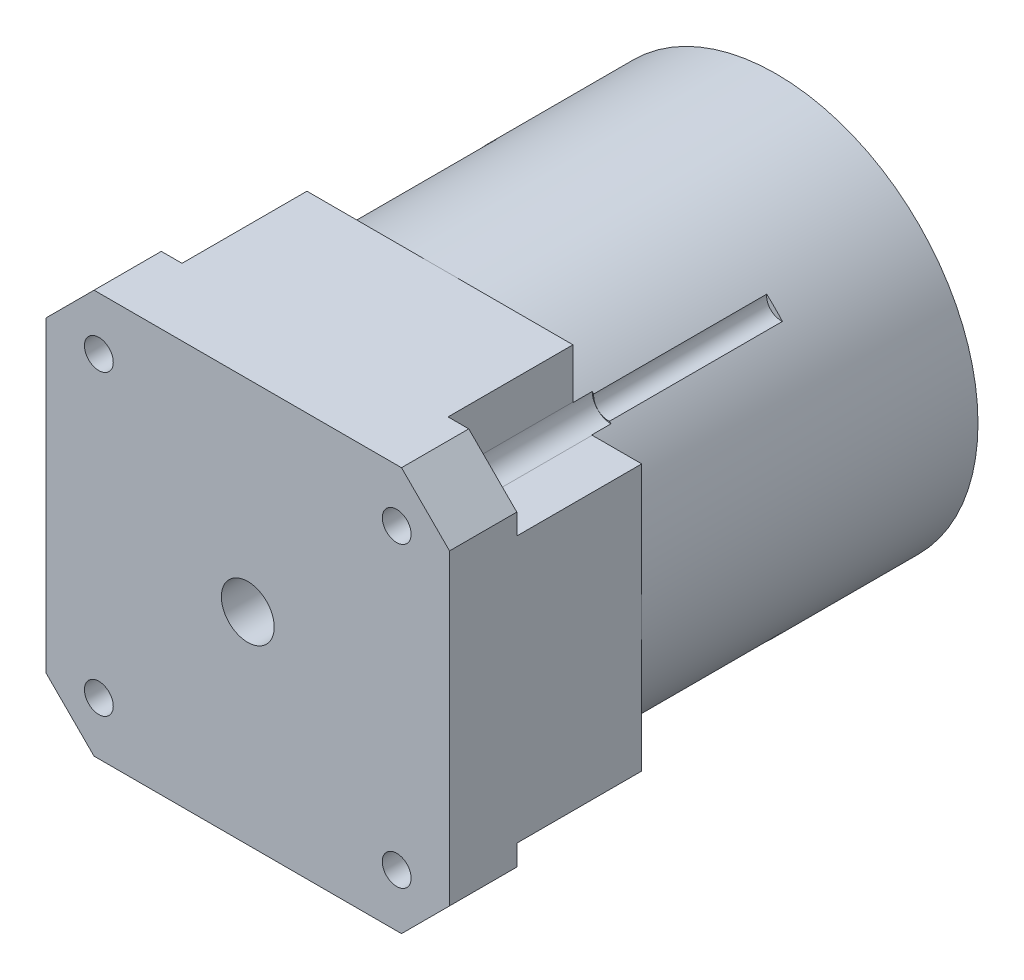
SolidWorks part; units mm, degrees
ref_plane "Front Plane" through (0, 0, 0) normal (0, 0, 1) x (1, 0, 0)
ref_plane "Top Plane" through (0, 0, 0) normal (0, 1, 0) x (1, 0, 0)
ref_plane "Right Plane" through (0, 0, 0) normal (1, 0, 0) x (0, 0, -1)
sketch "Sketch2" plane through (0, 0, 0) normal (0, 0, 1) x (1, 0, 0)
  circle A0 centre (0, 0) radius 21
  dimension "D1" = 42
extrude "Boss-Extrude1" add sketch "Sketch2" along normal blind 35
sketch "Sketch3" plane through (0, 0, 35) normal (0, 0, 1) x (1, 0, 0)
  line L1 (-21, -21) -> (21, -21)
  line L2 (-21, -21) -> (-21, 21)
  line L3 (-21, 21) -> (21, 21)
  line L4 (21, -21) -> (21, 21)
  line L5 (-21, -21) -> (21, 21) construction
  line L6 (-21, 21) -> (21, -21) construction
  point P0 (0, 0)
extrude "Boss-Extrude2" add sketch "Sketch3" along normal blind 20
chamfer "Chamfer1" distance 5 angle 45 4 edges at (-21, -21, 45) (21, -21, 45) (21, 21, 45) (-21, 21, 45)
sketch "Sketch4" plane through (0, 0, 35) normal (0, 0, -1) x (-1, 0, 0)
  line L0 (-14.9549, 0) -> (14.9549, 0) construction
  line L1 (0, 0) -> (0, 15.4444) construction
  circle A0 centre (15.5, 15.5) radius 1.5
  circle A1 centre (-15.5, 15.5) radius 1.5
  circle A2 centre (15.5, -15.5) radius 1.5
  circle A3 centre (-15.5, -15.5) radius 1.5
  point P6 (0, 0)
  dimension "D1" = 3
  dimension "D2" = 15.5
  dimension "D3" = 15.5
extrude "Cut-Extrude1" cut sketch "Sketch4" against normal through all and the other way blind 20
sketch "Sketch5" plane through (0, 0, 35) normal (0, 0, -1) x (-1, 0, 0)
  line L0 (21, 16) -> (16, 21) construction
  line L1 (15.8436, 13.8436) -> (23.1564, 13.8436)
  line L2 (13.8436, 15.8436) -> (13.8436, 23.1564)
  line L3 (13.8436, 23.1564) -> (23.1564, 23.1564)
  line L4 (23.1564, 13.8436) -> (23.1564, 23.1564)
  line L5 (13.8436, 13.8436) -> (23.1564, 23.1564) construction
  line L6 (13.8436, 23.1564) -> (23.1564, 13.8436) construction
  line L7 (0, 0) -> (0, 36.9408) construction
  line L8 (0, 0) -> (35.9646, 0) construction
  line L9 (13.8436, -23.1564) -> (23.1564, -13.8436) construction
  line L10 (13.8436, -13.8436) -> (23.1564, -23.1564) construction
  line L11 (23.1564, -13.8436) -> (23.1564, -23.1564)
  line L12 (13.8436, -23.1564) -> (23.1564, -23.1564)
  line L13 (13.8436, -15.8436) -> (13.8436, -23.1564)
  line L14 (15.8436, -13.8436) -> (23.1564, -13.8436)
  line L15 (-13.8436, 23.1564) -> (-23.1564, 13.8436) construction
  line L16 (-13.8436, 13.8436) -> (-23.1564, 23.1564) construction
  line L17 (-23.1564, 13.8436) -> (-23.1564, 23.1564)
  line L18 (-13.8436, 23.1564) -> (-23.1564, 23.1564)
  line L19 (-13.8436, 15.8436) -> (-13.8436, 23.1564)
  line L20 (-15.8436, 13.8436) -> (-23.1564, 13.8436)
  line L21 (-13.8436, -13.8436) -> (-23.1564, -23.1564) construction
  line L22 (-13.8436, -23.1564) -> (-23.1564, -13.8436) construction
  line L23 (-15.8436, -13.8436) -> (-23.1564, -13.8436)
  line L24 (-13.8436, -15.8436) -> (-13.8436, -23.1564)
  line L25 (-13.8436, -23.1564) -> (-23.1564, -23.1564)
  line L26 (-23.1564, -13.8436) -> (-23.1564, -23.1564)
  arc A0 (15.8436, 13.8436) -> (13.8436, 15.8436) centre (15.8436, 15.8436) cw
  arc A1 (15.8436, -13.8436) -> (13.8436, -15.8436) centre (15.8436, -15.8436) ccw
  arc A2 (-15.8436, 13.8436) -> (-13.8436, 15.8436) centre (-15.8436, 15.8436) ccw
  arc A3 (-15.8436, -13.8436) -> (-13.8436, -15.8436) centre (-15.8436, -15.8436) cw
  point P0 (18.5, 18.5)
  point P21 (18.5, -18.5)
  point P29 (-18.5, 18.5)
  point P37 (-18.5, -18.5)
  dimension "D1" = 2
extrude "Cut-Extrude2" cut sketch "Sketch5" against normal blind 15 from offset 2
sketch "Sketch6" plane through (0, 0, 0) normal (0, 0, -1) x (-1, 0, 0)
  circle A0 centre (0, 0) radius 2.75
  dimension "D1" = 5.5
extrude "Cut-Extrude3" cut sketch "Sketch6" against normal through all
sketch "Sketch8" plane through (0, 0, 0) normal (0, 0, -1) x (-1, 0, 0)
  line L0 (0, -42.0616) -> (0, 42.0616) construction
  line L1 (-50.0671, 0) -> (50.0671, 0) construction
  circle A0 centre (0, 17.5) radius 2
  circle A1 centre (17.5, 0) radius 2
  circle A2 centre (0, -17.5) radius 2
  circle A3 centre (-17.5, 0) radius 2
  point P5 (0, 0)
  point P10 (0, 0)
  point P21 (0, 0)
  dimension "D1" = 4
  dimension "D2" = 17.5
  dimension "D3" = 4
extrude "Cut-Extrude4" cut sketch "Sketch8" against normal blind 8
sketch "Sketch9" plane through (0, 0, 0) normal (0, 0, -1) x (-1, 0, 0)
  circle A0 centre (0, 0) radius 9.6281
  circle A1 centre (0, 0) radius 2.75
extrude "Boss-Extrude3" add sketch "Sketch9" along normal blind 2
